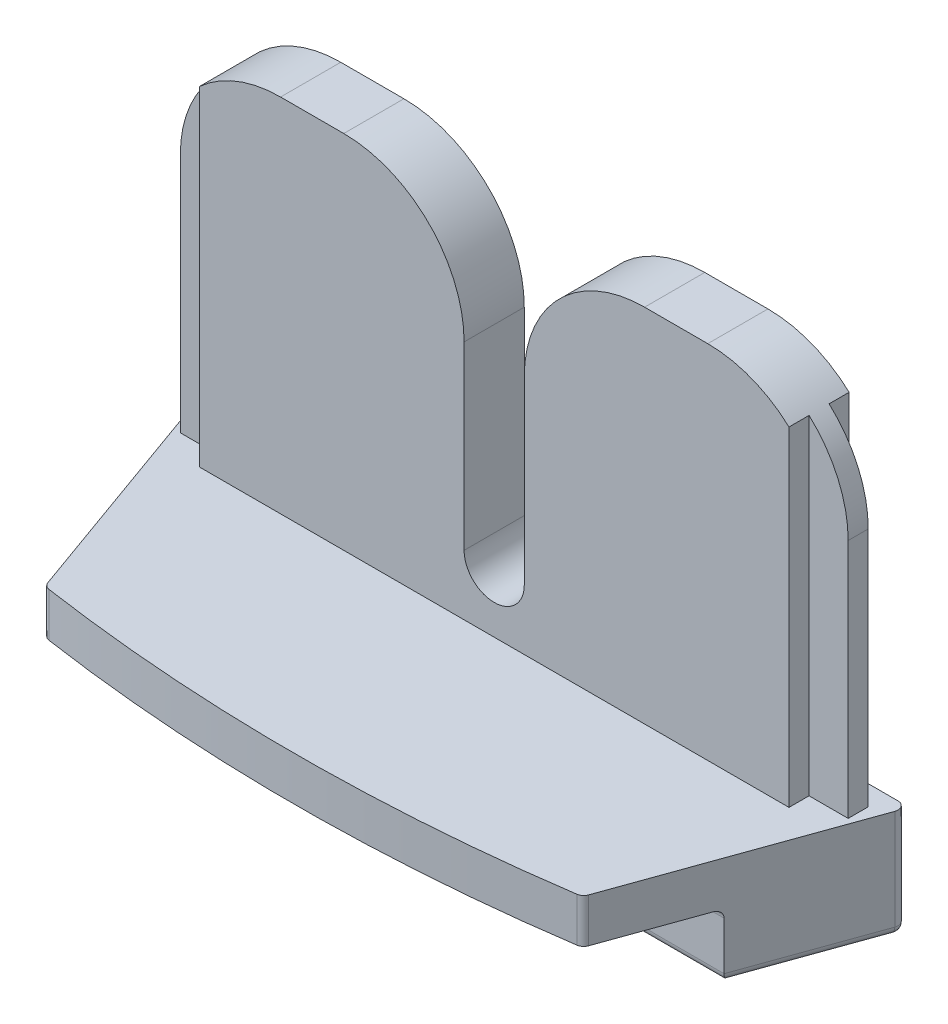
SolidWorks part; units mm, degrees
ref_plane "Front Plane" through (0, 0, 0) normal (0, 0, 1) x (1, 0, 0)
ref_plane "Top Plane" through (0, 0, 0) normal (0, 1, 0) x (1, 0, 0)
ref_plane "Right Plane" through (0, 0, 0) normal (1, 0, 0) x (0, 0, -1)
sketch "Sketch1" plane through (0, 0, 0) normal (0, 0, 1) x (1, 0, 0)
  line L0 (21.1455, 0) -> (21.1455, 1.905) construction
  line L1 (0, 0) -> (42.291, 0)
  line L2 (0, 0) -> (0, 22.86)
  line L3 (0, 22.86) -> (19.2405, 22.86)
  line L4 (42.291, 0) -> (42.291, 22.86)
  line L5 (19.2405, 22.86) -> (19.2405, 3.81)
  line L6 (23.0505, 22.86) -> (42.291, 22.86)
  line L7 (23.0505, 3.81) -> (23.0505, 22.86)
  arc A0 (19.2405, 3.81) -> (23.0505, 3.81) centre (21.1455, 3.81) ccw
  dimension "D3" = 3.81
  dimension "D1" = 42.291
  dimension "D2" = 22.86
  dimension "D4" = 3.81
extrude "Boss-Extrude1" add sketch "Sketch1" along normal blind 1.27
sketch "Sketch2" plane through (0, 0, 0) normal (0, 0, -1) x (-1, 0, 0)
  line L0 (0, 0) -> (-42.291, 0) construction
  line L1 (-23.0505, 22.86) -> (-39.8145, 22.86)
  line L2 (-23.0505, 22.86) -> (-23.0505, 3.81)
  line L3 (-23.0505, 0) -> (-39.8145, 0)
  line L4 (-39.8145, 22.86) -> (-39.8145, 0)
  line L5 (-23.0505, 0) -> (-19.2405, 0)
  line L6 (-19.2405, 22.86) -> (-2.4765, 22.86)
  line L7 (-19.2405, 22.86) -> (-19.2405, 3.81)
  line L8 (-19.2405, 0) -> (-2.4765, 0)
  line L9 (-2.4765, 22.86) -> (-2.4765, 0)
  arc A0 (-23.0505, 3.81) -> (-19.2405, 3.81) centre (-21.1455, 3.81) ccw
  arc A1 (-23.0505, 3.81) -> (-19.2405, 3.81) centre (-21.1455, 3.81) ccw construction
  dimension "D1" = 16.764
  dimension "D2" = 16.764
extrude "Boss-Extrude2" add sketch "Sketch2" along normal blind 1.27
sketch "Sketch3" plane through (0, 0, 1.27) normal (0, 0, 1) x (1, 0, 0)
  line L0 (0, 0) -> (42.291, 0) construction
  line L1 (19.2405, 22.86) -> (2.4765, 22.86)
  line L2 (19.2405, 22.86) -> (19.2405, 3.81)
  line L3 (19.2405, 0) -> (2.4765, 0)
  line L4 (2.4765, 22.86) -> (2.4765, 0)
  line L5 (39.8145, 22.86) -> (39.8145, 0) construction
  line L6 (23.0505, 22.86) -> (39.8145, 22.86)
  line L7 (23.0505, 22.86) -> (23.0505, 3.81)
  line L8 (23.0505, 0) -> (39.8145, 0)
  line L9 (39.8145, 22.86) -> (39.8145, 0)
  line L10 (2.4765, 0) -> (2.4765, 22.86) construction
  line L11 (19.2405, 0) -> (23.0505, 0)
  arc A0 (19.2405, 3.81) -> (23.0505, 3.81) centre (21.1455, 3.81) ccw
  arc A1 (19.2405, 3.81) -> (23.0505, 3.81) centre (21.1455, 3.81) ccw construction
extrude "Boss-Extrude3" add sketch "Sketch3" along normal blind 1.27
sketch "Sketch5" plane through (0, 0, 0) normal (0, -1, 0) x (1, 0, 0)
  line L0 (-1.3335, -1.27) -> (43.6245, -1.27)
  line L1 (21.1455, 13.9646) -> (21.1455, -1.27) construction
  line L3 (39.8145, -1.27) -> (2.4765, -1.27) construction
  line L5 (4.1275, 13.97) -> (-1.3335, -1.27)
  line L6 (38.1635, 13.97) -> (43.6245, -1.27)
  line L7 (0, 15.24) -> (48.39, 15.24) construction
  arc A0 (4.1275, 13.97) -> (38.1635, 13.97) centre (21.1455, -99.4156) cw
  point P7 (21.1455, -1.27)
  point P8 (21.1455, -1.27)
  dimension "D4" = 16.51
  dimension "D1" = 44.958
  dimension "D2" = 34.036
  dimension "D3" = 15.24
extrude "Boss-Extrude4" add sketch "Sketch5" along normal blind 2.794
sketch "Sketch6" plane through (0, -2.794, 0) normal (0, -1, 0) x (1, 0, 0)
  line L0 (1.7611, 7.366) -> (13.9065, 7.366)
  line L1 (4.1275, 13.97) -> (-1.3335, -1.27) construction
  line L2 (43.6245, -1.27) -> (38.1635, 13.97) construction
  line L3 (-1.3335, -1.27) -> (43.6245, -1.27) construction
  line L4 (-1.3335, -1.27) -> (13.9065, -1.27)
  line L5 (13.9065, -1.27) -> (13.9065, 7.366)
  line L6 (28.3845, -1.27) -> (43.6245, -1.27)
  line L7 (28.3845, 7.366) -> (40.5299, 7.366)
  line L8 (28.3845, -1.27) -> (28.3845, 7.366)
  line L9 (1.7611, 7.366) -> (-1.3335, -1.27)
  line L10 (40.5299, 7.366) -> (43.6245, -1.27)
  dimension "D1" = 8.636
  dimension "D2" = 15.24
extrude "Boss-Extrude5" add sketch "Sketch6" along normal blind 4.064
fillet "Fillet1" radius 0.508 19 edges at (28.3845, -2.794, 3.048) (34.4572, -2.794, 7.366) (36.0045, -6.858, -1.27) (28.3845, -6.858, 3.048) (34.4572, -6.858, 7.366) (42.0772, -6.858, 3.048) (7.8338, -6.858, 7.366) (13.9065, -6.858, 3.048) (6.2865, -6.858, -1.27) (0.2138, -6.858, 3.048) (-1.3335, -3.429, -1.27) (28.3845, -4.826, -1.27) (43.6245, -3.429, -1.27) (38.1635, -1.397, 13.97) (4.1275, -1.397, 13.97)
fillet "Fillet3" radius 7.62 4 edges at (23.0505, 22.86, 0.635) (19.2405, 22.86, 0.635) (0, 22.86, 0.635) (42.291, 22.86, 0.635)
